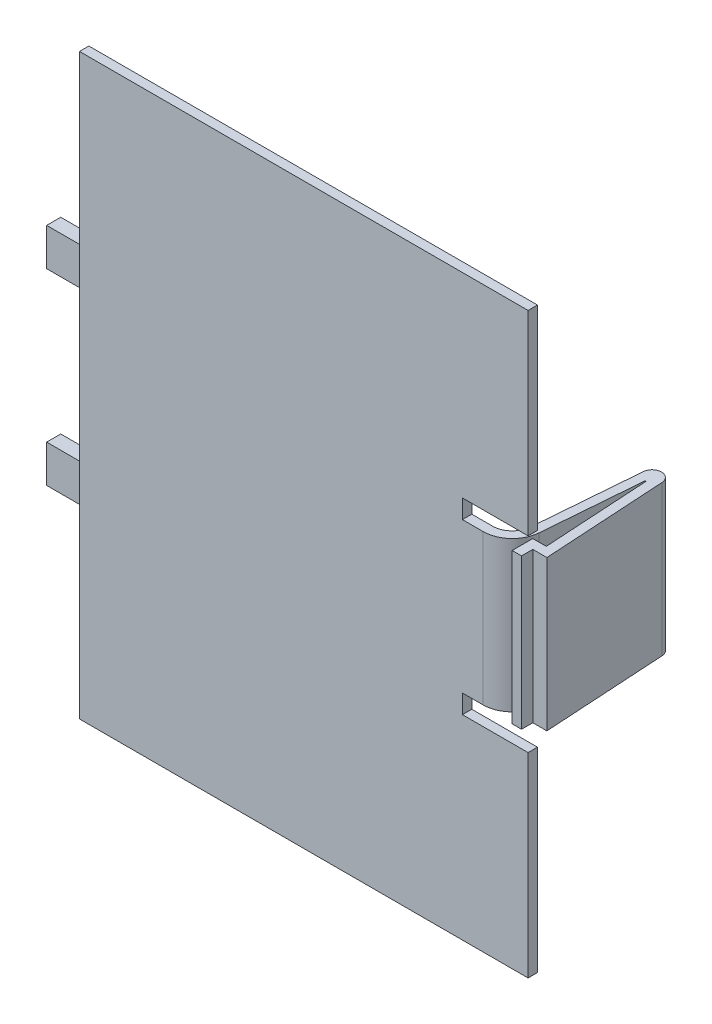
SolidWorks part; units mm, degrees
ref_plane "Front Plane" through (0, 0, 0) normal (0, 0, 1) x (1, 0, 0)
ref_plane "Top Plane" through (0, 0, 0) normal (0, 1, 0) x (1, 0, 0)
ref_plane "Right Plane" through (0, 0, 0) normal (1, 0, 0) x (0, 0, -1)
sketch "Sketch1" plane through (0, 0, 0) normal (0, 0, 1) x (1, 0, 0)
  line L1 (-110.8, 0) -> (-63, 0) construction
  line L3 (-70, -10) -> (-63, -10)
  line L4 (-70, -10) -> (-70, 10)
  line L5 (-110.8, -30.8) -> (-63, -30.8)
  line L6 (-110.8, 30.8) -> (-110.8, -30.8)
  line L7 (-63, 30.8) -> (-110.8, 30.8)
  line L8 (-63, -30.8) -> (-63, 30.8)
  line L9 (-110.8, -30.8) -> (-63, -30.8)
  line L10 (-110.8, 30.8) -> (-110.8, -30.8)
  line L11 (-63, 30.8) -> (-110.8, 30.8)
  line L12 (-63, -30.8) -> (-63, 30.8)
  line L13 (-70, 10) -> (-63, 10)
  line L14 (-63, -10) -> (-63, 10)
  line L15 (-70, -10) -> (-63, 10) construction
  line L16 (-70, 10) -> (-63, -10) construction
  point P4 (-66.5, 0)
  dimension "D2" = 20
  dimension "D3" = 7
  dimension "D1" = 0
extrude "Boss-Extrude1" add sketch "Sketch1" against normal blind 1 contours L4 L13 L12 L11 L10 L9 L3
sketch "Sketch2" plane through (0, 0, -1) normal (0, 0, -1) x (-1, 0, 0)
  line L0 (120, -10) -> (101.3621, -10) construction
  line L1 (120, -40) -> (120, 40) construction
  line L2 (120, 10) -> (100.0679, 10) construction
  line L3 (109.55, 0) -> (65.45, 0) construction
  line L4 (110.8, 30.8) -> (110.8, -30.8) construction
  line L5 (115.3, -8) -> (106.3, -8)
  line L6 (115.3, -8) -> (115.3, -12)
  line L7 (115.3, -12) -> (106.3, -12)
  line L8 (106.3, -8) -> (106.3, -12)
  line L9 (115.3, -8) -> (106.3, -12) construction
  line L10 (115.3, -12) -> (106.3, -8) construction
  line L12 (115.3, 12) -> (106.3, 12)
  line L13 (115.3, 12) -> (115.3, 8)
  line L14 (115.3, 8) -> (106.3, 8)
  line L15 (106.3, 12) -> (106.3, 8)
  line L16 (115.3, 12) -> (106.3, 8) construction
  line L17 (115.3, 8) -> (106.3, 12) construction
  point P8 (110.8, -10)
  point P15 (110.8, 10)
  dimension "D1" = 10
  dimension "D2" = 10
  dimension "D3" = 4
  dimension "D4" = 9
extrude "Boss-Extrude2" add sketch "Sketch2" along normal blind 1.5
sketch "Sketch3" plane through (0, -10, 0) normal (0, 1, 0) x (1, 0, 0)
  line L0 (-70, 1) -> (-70, 0) construction
  line L1 (-70, 1) -> (-70, 0)
  line L2 (-70, 1) -> (-67.7876, 1)
  line L3 (-109.55, 1) -> (-65.45, 1) construction
  line L4 (-65.6885, 2.9359) -> (-64.7856, 14.0808)
  line L5 (-62.7907, 14.0604) -> (-62, 1)
  line L6 (-62, 1) -> (-63.5, 1)
  line L7 (-63.5, 1) -> (-63.5, -0.2)
  line L8 (-63.5, -0.2) -> (-64.5, -0.2)
  line L9 (-64.5, -0.2) -> (-64.5, 2)
  line L10 (-64.5, 2) -> (-63.0624, 2)
  line L11 (-63.0624, 2) -> (-63.7466, 13.303)
  line L12 (-63.8452, 13.304) -> (-64.6918, 2.8551)
  line L13 (-110.8, 0) -> (-63, 0) construction
  line L14 (-67.7876, 0) -> (-70, 0)
  line L15 (-110.8, 1) -> (-63, 1) construction
  line L16 (-63, 1) -> (-63, 0) construction
  line L17 (-60, 0) -> (-120, 0) construction
  arc A0 (-67.7876, 1) -> (-65.6885, 2.9359) centre (-67.7876, 3.106) ccw
  arc A1 (-64.7856, 14.0808) -> (-62.7907, 14.0604) centre (-63.7888, 14) cw
  arc A2 (-63.7466, 13.303) -> (-63.8452, 13.304) centre (-63.796, 13.3) ccw
  arc A3 (-64.6918, 2.8551) -> (-67.7876, 0) centre (-67.7876, 3.106) cw
  point P26 (-63.0353, 1.8352)
  point P27 (-62.2745, 1)
  point P30 (-69.4583, 1)
  point P31 (-62.6411, 12.2188)
  point P32 (-64.3255, 11.7971)
  point P33 (-62, 11.5418)
  point P34 (-62.26, 11.8425)
  point P35 (-63.5, 11.6377)
  point P36 (-63.3199, 10.9713)
  point P37 (-63.2409, 12.693)
  point P38 (0, 0)
  point P39 (-65.8716, 4.4899)
  point P40 (-69.8629, 1)
  point P41 (-64.3931, 12.6195)
  point P42 (-65.2825, 5.2437)
  point P43 (-69.8, 1)
  point P44 (-68.8954, 0)
  point P47 (-66.3474, 1.8408)
  point P48 (-66.8691, 1)
  point P49 (-67.3481, 0)
  point P50 (-65.6878, 2.8692)
  point P51 (-63.8478, 13.2729)
  dimension "D1" = 1
  dimension "D8" = 15
  dimension "D7" = 0.7
  dimension "D2" = 1.2
  dimension "D3" = 1
  dimension "D4" = 1
  dimension "D5" = 0.5
  dimension "D6" = 1
sketch "Sketch4" plane through (0, 0, 0) normal (0, 1, 0) x (1, 0, 0)
  line L12 (-63.7466, 13.303) -> (-63.0624, 2)
  line L13 (-64.6918, 2.8551) -> (-63.8452, 13.304)
  line L14 (-70, 0) -> (-67.7876, 0)
  line L15 (-70, 1) -> (-70, 0)
  line L16 (-67.7876, 1) -> (-70, 1)
  line L17 (-64.7856, 14.0808) -> (-65.6885, 2.9359)
  line L18 (-62, 1) -> (-62.7907, 14.0604)
  line L19 (-63.5, 1) -> (-62, 1)
  line L20 (-63.5, -0.2) -> (-63.5, 1)
  line L21 (-64.5, -0.2) -> (-63.5, -0.2)
  line L22 (-64.5, 2) -> (-64.5, -0.2)
  line L23 (-63.0624, 2) -> (-64.5, 2)
  line L24 (-63.7466, 13.303) -> (-63.0624, 2)
  line L25 (-64.6918, 2.8551) -> (-63.8452, 13.304)
  line L26 (-70, 0) -> (-67.7876, 0)
  line L27 (-70, 1) -> (-70, 0)
  line L28 (-67.7876, 1) -> (-70, 1)
  line L29 (-64.7856, 14.0808) -> (-65.6885, 2.9359)
  line L30 (-62, 1) -> (-62.7907, 14.0604)
  line L31 (-63.5, 1) -> (-62, 1)
  line L32 (-63.5, -0.2) -> (-63.5, 1)
  line L33 (-64.5, -0.2) -> (-63.5, -0.2)
  line L34 (-64.5, 2) -> (-64.5, -0.2)
  line L35 (-63.0624, 2) -> (-64.5, 2)
  arc A4 (-63.7466, 13.303) -> (-63.8452, 13.304) centre (-63.796, 13.3) ccw
  arc A5 (-67.7876, 0) -> (-64.6918, 2.8551) centre (-67.7876, 3.106) ccw
  arc A6 (-67.7876, 1) -> (-65.6885, 2.9359) centre (-67.7876, 3.106) ccw
  arc A7 (-62.7907, 14.0604) -> (-64.7856, 14.0808) centre (-63.7888, 14) ccw
  arc A8 (-63.7466, 13.303) -> (-63.8452, 13.304) centre (-63.796, 13.3) ccw
  arc A9 (-67.7876, 0) -> (-64.6918, 2.8551) centre (-67.7876, 3.106) ccw
  arc A10 (-67.7876, 1) -> (-65.6885, 2.9359) centre (-67.7876, 3.106) ccw
  arc A11 (-62.7907, 14.0604) -> (-64.7856, 14.0808) centre (-63.7888, 14) ccw
  dimension "D1" = 0
extrude "Boss-Extrude5" add sketch "Sketch4" along normal blind 8 and the other way blind 8
